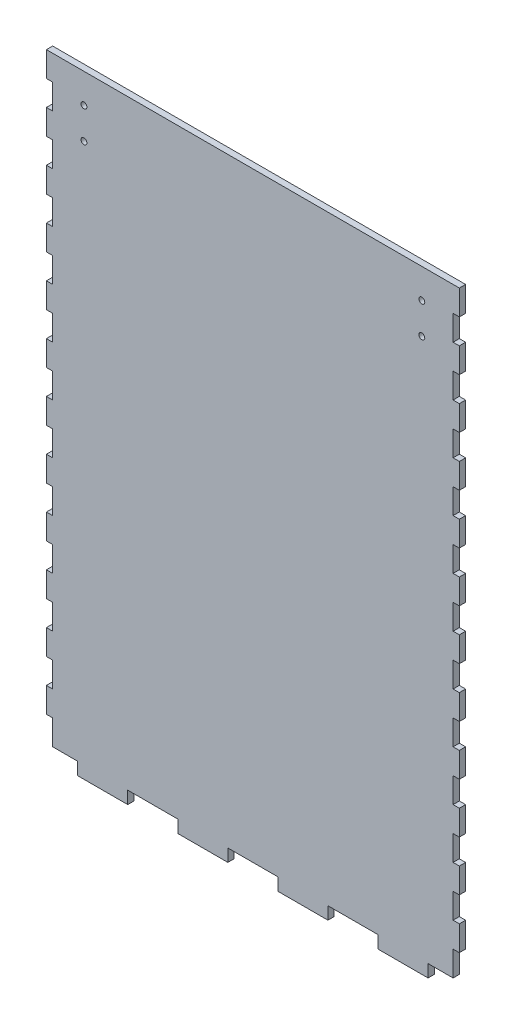
SolidWorks part; units mm, degrees
ref_plane "Front Plane" through (0, 0, 0) normal (0, 0, 1) x (1, 0, 0)
ref_plane "Top Plane" through (0, 0, 0) normal (0, 1, 0) x (1, 0, 0)
ref_plane "Right Plane" through (0, 0, 0) normal (1, 0, 0) x (0, 0, -1)
sketch "Sketch1" plane through (0, 0, 0) normal (0, 0, 1) x (1, 0, 0)
  line L0 (0, 0) -> (203.2, 0)
  line L1 (203.2, 0) -> (203.2, 304.8)
  line L2 (203.2, 304.8) -> (0, 304.8)
  line L3 (0, 304.8) -> (0, 0)
  dimension "D1" = 203.2
  dimension "D2" = 304.8
extrude "Boss-Extrude1" add sketch "Sketch1" along normal blind 3.175
sketch "Sketch2" plane through (0, 0, 3.175) normal (0, 0, 1) x (1, 0, 0)
  line L0 (0, 304.8) -> (-3.175, 304.8)
  line L1 (-3.175, 304.8) -> (-3.175, 292.1)
  line L2 (-3.175, 292.1) -> (0, 292.1)
  line L3 (0, 304.8) -> (0, 0) construction
  line L4 (0, 292.1) -> (0, 304.8)
  line L5 (101.6, 304.8) -> (101.6, 0) construction
  line L6 (203.2, 304.8) -> (0, 304.8) construction
  line L7 (0, 0) -> (203.2, 0) construction
  line L8 (206.375, 292.1) -> (203.2, 292.1)
  line L9 (206.375, 304.8) -> (206.375, 292.1)
  line L10 (203.2, 304.8) -> (206.375, 304.8)
  line L11 (203.2, 292.1) -> (203.2, 304.8)
  line L12 (0, 266.7) -> (0, 279.4)
  line L13 (0, 279.4) -> (-3.175, 279.4)
  line L14 (-3.175, 279.4) -> (-3.175, 266.7)
  line L15 (-3.175, 266.7) -> (0, 266.7)
  line L16 (206.375, 266.7) -> (203.2, 266.7)
  line L17 (203.2, 266.7) -> (203.2, 279.4)
  line L18 (203.2, 279.4) -> (206.375, 279.4)
  line L19 (206.375, 279.4) -> (206.375, 266.7)
  line L20 (0, 241.3) -> (0, 254)
  line L21 (0, 254) -> (-3.175, 254)
  line L22 (-3.175, 254) -> (-3.175, 241.3)
  line L23 (-3.175, 241.3) -> (0, 241.3)
  line L24 (206.375, 241.3) -> (203.2, 241.3)
  line L25 (203.2, 241.3) -> (203.2, 254)
  line L26 (203.2, 254) -> (206.375, 254)
  line L27 (206.375, 254) -> (206.375, 241.3)
  line L28 (0, 215.9) -> (0, 228.6)
  line L29 (0, 228.6) -> (-3.175, 228.6)
  line L30 (-3.175, 228.6) -> (-3.175, 215.9)
  line L31 (-3.175, 215.9) -> (0, 215.9)
  line L32 (206.375, 215.9) -> (203.2, 215.9)
  line L33 (203.2, 215.9) -> (203.2, 228.6)
  line L34 (203.2, 228.6) -> (206.375, 228.6)
  line L35 (206.375, 228.6) -> (206.375, 215.9)
  line L36 (0, 190.5) -> (0, 203.2)
  line L37 (0, 203.2) -> (-3.175, 203.2)
  line L38 (-3.175, 203.2) -> (-3.175, 190.5)
  line L39 (-3.175, 190.5) -> (0, 190.5)
  line L40 (206.375, 190.5) -> (203.2, 190.5)
  line L41 (203.2, 190.5) -> (203.2, 203.2)
  line L42 (203.2, 203.2) -> (206.375, 203.2)
  line L43 (206.375, 203.2) -> (206.375, 190.5)
  line L44 (0, 165.1) -> (0, 177.8)
  line L45 (0, 177.8) -> (-3.175, 177.8)
  line L46 (-3.175, 177.8) -> (-3.175, 165.1)
  line L47 (-3.175, 165.1) -> (0, 165.1)
  line L48 (206.375, 165.1) -> (203.2, 165.1)
  line L49 (203.2, 165.1) -> (203.2, 177.8)
  line L50 (203.2, 177.8) -> (206.375, 177.8)
  line L51 (206.375, 177.8) -> (206.375, 165.1)
  line L52 (0, 139.7) -> (0, 152.4)
  line L53 (0, 152.4) -> (-3.175, 152.4)
  line L54 (-3.175, 152.4) -> (-3.175, 139.7)
  line L55 (-3.175, 139.7) -> (0, 139.7)
  line L56 (206.375, 139.7) -> (203.2, 139.7)
  line L57 (203.2, 139.7) -> (203.2, 152.4)
  line L58 (203.2, 152.4) -> (206.375, 152.4)
  line L59 (206.375, 152.4) -> (206.375, 139.7)
  line L60 (0, 114.3) -> (0, 127)
  line L61 (0, 127) -> (-3.175, 127)
  line L62 (-3.175, 127) -> (-3.175, 114.3)
  line L63 (-3.175, 114.3) -> (0, 114.3)
  line L64 (206.375, 114.3) -> (203.2, 114.3)
  line L65 (203.2, 114.3) -> (203.2, 127)
  line L66 (203.2, 127) -> (206.375, 127)
  line L67 (206.375, 127) -> (206.375, 114.3)
  line L68 (0, 88.9) -> (0, 101.6)
  line L69 (0, 101.6) -> (-3.175, 101.6)
  line L70 (-3.175, 101.6) -> (-3.175, 88.9)
  line L71 (-3.175, 88.9) -> (0, 88.9)
  line L72 (206.375, 88.9) -> (203.2, 88.9)
  line L73 (203.2, 88.9) -> (203.2, 101.6)
  line L74 (203.2, 101.6) -> (206.375, 101.6)
  line L75 (206.375, 101.6) -> (206.375, 88.9)
  line L76 (0, 63.5) -> (0, 76.2)
  line L77 (0, 76.2) -> (-3.175, 76.2)
  line L78 (-3.175, 76.2) -> (-3.175, 63.5)
  line L79 (-3.175, 63.5) -> (0, 63.5)
  line L80 (206.375, 63.5) -> (203.2, 63.5)
  line L81 (203.2, 63.5) -> (203.2, 76.2)
  line L82 (203.2, 76.2) -> (206.375, 76.2)
  line L83 (206.375, 76.2) -> (206.375, 63.5)
  line L84 (0, 38.1) -> (0, 50.8)
  line L85 (0, 50.8) -> (-3.175, 50.8)
  line L86 (-3.175, 50.8) -> (-3.175, 38.1)
  line L87 (-3.175, 38.1) -> (0, 38.1)
  line L88 (206.375, 38.1) -> (203.2, 38.1)
  line L89 (203.2, 38.1) -> (203.2, 50.8)
  line L90 (203.2, 50.8) -> (206.375, 50.8)
  line L91 (206.375, 50.8) -> (206.375, 38.1)
  line L92 (0, 12.7) -> (0, 25.4)
  line L93 (0, 25.4) -> (-3.175, 25.4)
  line L94 (-3.175, 25.4) -> (-3.175, 12.7)
  line L95 (-3.175, 12.7) -> (0, 12.7)
  line L96 (206.375, 12.7) -> (203.2, 12.7)
  line L97 (203.2, 12.7) -> (203.2, 25.4)
  line L98 (203.2, 25.4) -> (206.375, 25.4)
  line L99 (206.375, 25.4) -> (206.375, 12.7)
  line L100 (0, 292.1) -> (0, 266.7) construction
  line L101 (12.7, 0) -> (12.7, -6.35)
  line L102 (12.7, -6.35) -> (38.1, -6.35)
  line L103 (38.1, -6.35) -> (38.1, 0)
  line L104 (38.1, 0) -> (12.7, 0)
  line L105 (88.9, 0) -> (63.5, 0)
  line L106 (63.5, 0) -> (63.5, -6.35)
  line L107 (63.5, -6.35) -> (88.9, -6.35)
  line L108 (88.9, -6.35) -> (88.9, 0)
  line L109 (139.7, 0) -> (114.3, 0)
  line L110 (114.3, 0) -> (114.3, -6.35)
  line L111 (114.3, -6.35) -> (139.7, -6.35)
  line L112 (139.7, -6.35) -> (139.7, 0)
  line L113 (190.5, 0) -> (165.1, 0)
  line L114 (165.1, 0) -> (165.1, -6.35)
  line L115 (165.1, -6.35) -> (190.5, -6.35)
  line L116 (190.5, -6.35) -> (190.5, 0)
  line L117 (38.1, 0) -> (88.9, 0) construction
  dimension "D1" = 3.175
  dimension "D2" = 12.7
  dimension "D4" = 25.4
  dimension "D5" = 12.7
  dimension "D6" = 6.35
  dimension "D7" = 25.4
  dimension "D9" = 50.8
  dimension "D3" = 12
  dimension "D8" = 4
extrude "Boss-Extrude2" add sketch "Sketch2" against normal up to surface (3.175 mm away) up to face at (101.6, 152.4, 0)
sketch "Sketch3" [suppressed] plane through (0, 0, 3.175) normal (0, 0, 1) x (1, 0, 0)
  line L0 (0, 0) -> (-3.175, 0)
  line L1 (-3.175, 0) -> (-3.175, 12.7)
  line L2 (-3.175, 12.7) -> (0, 12.7)
  line L3 (0, 304.8) -> (0, 0) construction
  line L4 (0, 12.7) -> (0, 0)
  line L5 (101.6, 304.8) -> (101.6, 0) construction
  line L6 (203.2, 304.8) -> (0, 304.8) construction
  line L7 (0, 0) -> (203.2, 0) construction
  line L8 (206.375, 12.7) -> (203.2, 12.7)
  line L9 (206.375, 0) -> (206.375, 12.7)
  line L10 (203.2, 0) -> (206.375, 0)
  line L11 (203.2, 12.7) -> (203.2, 0)
  line L12 (0, 38.1) -> (0, 25.4)
  line L13 (0, 25.4) -> (-3.175, 25.4)
  line L14 (-3.175, 25.4) -> (-3.175, 38.1)
  line L15 (-3.175, 38.1) -> (0, 38.1)
  line L16 (206.375, 38.1) -> (203.2, 38.1)
  line L17 (203.2, 38.1) -> (203.2, 25.4)
  line L18 (203.2, 25.4) -> (206.375, 25.4)
  line L19 (206.375, 25.4) -> (206.375, 38.1)
  line L20 (0, 63.5) -> (0, 50.8)
  line L21 (0, 50.8) -> (-3.175, 50.8)
  line L22 (-3.175, 50.8) -> (-3.175, 63.5)
  line L23 (-3.175, 63.5) -> (0, 63.5)
  line L24 (206.375, 63.5) -> (203.2, 63.5)
  line L25 (203.2, 63.5) -> (203.2, 50.8)
  line L26 (203.2, 50.8) -> (206.375, 50.8)
  line L27 (206.375, 50.8) -> (206.375, 63.5)
  line L28 (0, 88.9) -> (0, 76.2)
  line L29 (0, 76.2) -> (-3.175, 76.2)
  line L30 (-3.175, 76.2) -> (-3.175, 88.9)
  line L31 (-3.175, 88.9) -> (0, 88.9)
  line L32 (206.375, 88.9) -> (203.2, 88.9)
  line L33 (203.2, 88.9) -> (203.2, 76.2)
  line L34 (203.2, 76.2) -> (206.375, 76.2)
  line L35 (206.375, 76.2) -> (206.375, 88.9)
  line L36 (0, 114.3) -> (0, 101.6)
  line L37 (0, 101.6) -> (-3.175, 101.6)
  line L38 (-3.175, 101.6) -> (-3.175, 114.3)
  line L39 (-3.175, 114.3) -> (0, 114.3)
  line L40 (206.375, 114.3) -> (203.2, 114.3)
  line L41 (203.2, 114.3) -> (203.2, 101.6)
  line L42 (203.2, 101.6) -> (206.375, 101.6)
  line L43 (206.375, 101.6) -> (206.375, 114.3)
  line L44 (0, 139.7) -> (0, 127)
  line L45 (0, 127) -> (-3.175, 127)
  line L46 (-3.175, 127) -> (-3.175, 139.7)
  line L47 (-3.175, 139.7) -> (0, 139.7)
  line L48 (206.375, 139.7) -> (203.2, 139.7)
  line L49 (203.2, 139.7) -> (203.2, 127)
  line L50 (203.2, 127) -> (206.375, 127)
  line L51 (206.375, 127) -> (206.375, 139.7)
  line L52 (0, 165.1) -> (0, 152.4)
  line L53 (0, 152.4) -> (-3.175, 152.4)
  line L54 (-3.175, 152.4) -> (-3.175, 165.1)
  line L55 (-3.175, 165.1) -> (0, 165.1)
  line L56 (206.375, 165.1) -> (203.2, 165.1)
  line L57 (203.2, 165.1) -> (203.2, 152.4)
  line L58 (203.2, 152.4) -> (206.375, 152.4)
  line L59 (206.375, 152.4) -> (206.375, 165.1)
  line L60 (0, 190.5) -> (0, 177.8)
  line L61 (0, 177.8) -> (-3.175, 177.8)
  line L62 (-3.175, 177.8) -> (-3.175, 190.5)
  line L63 (-3.175, 190.5) -> (0, 190.5)
  line L64 (206.375, 190.5) -> (203.2, 190.5)
  line L65 (203.2, 190.5) -> (203.2, 177.8)
  line L66 (203.2, 177.8) -> (206.375, 177.8)
  line L67 (206.375, 177.8) -> (206.375, 190.5)
  line L68 (0, 215.9) -> (0, 203.2)
  line L69 (0, 203.2) -> (-3.175, 203.2)
  line L70 (-3.175, 203.2) -> (-3.175, 215.9)
  line L71 (-3.175, 215.9) -> (0, 215.9)
  line L72 (206.375, 215.9) -> (203.2, 215.9)
  line L73 (203.2, 215.9) -> (203.2, 203.2)
  line L74 (203.2, 203.2) -> (206.375, 203.2)
  line L75 (206.375, 203.2) -> (206.375, 215.9)
  line L76 (0, 241.3) -> (0, 228.6)
  line L77 (0, 228.6) -> (-3.175, 228.6)
  line L78 (-3.175, 228.6) -> (-3.175, 241.3)
  line L79 (-3.175, 241.3) -> (0, 241.3)
  line L80 (206.375, 241.3) -> (203.2, 241.3)
  line L81 (203.2, 241.3) -> (203.2, 228.6)
  line L82 (203.2, 228.6) -> (206.375, 228.6)
  line L83 (206.375, 228.6) -> (206.375, 241.3)
  line L84 (0, 266.7) -> (0, 254)
  line L85 (0, 254) -> (-3.175, 254)
  line L86 (-3.175, 254) -> (-3.175, 266.7)
  line L87 (-3.175, 266.7) -> (0, 266.7)
  line L88 (206.375, 266.7) -> (203.2, 266.7)
  line L89 (203.2, 266.7) -> (203.2, 254)
  line L90 (203.2, 254) -> (206.375, 254)
  line L91 (206.375, 254) -> (206.375, 266.7)
  line L92 (0, 292.1) -> (0, 279.4)
  line L93 (0, 279.4) -> (-3.175, 279.4)
  line L94 (-3.175, 279.4) -> (-3.175, 292.1)
  line L95 (-3.175, 292.1) -> (0, 292.1)
  line L96 (206.375, 292.1) -> (203.2, 292.1)
  line L97 (203.2, 292.1) -> (203.2, 279.4)
  line L98 (203.2, 279.4) -> (206.375, 279.4)
  line L99 (206.375, 279.4) -> (206.375, 292.1)
  line L100 (0, 12.7) -> (0, 38.1) construction
  line L101 (12.7, 0) -> (12.7, -6.35)
  line L102 (12.7, -6.35) -> (38.1, -6.35)
  line L103 (38.1, -6.35) -> (38.1, 0)
  line L104 (38.1, 0) -> (12.7, 0)
  line L105 (88.9, 0) -> (63.5, 0)
  line L106 (63.5, 0) -> (63.5, -6.35)
  line L107 (63.5, -6.35) -> (88.9, -6.35)
  line L108 (88.9, -6.35) -> (88.9, 0)
  line L109 (139.7, 0) -> (114.3, 0)
  line L110 (114.3, 0) -> (114.3, -6.35)
  line L111 (114.3, -6.35) -> (139.7, -6.35)
  line L112 (139.7, -6.35) -> (139.7, 0)
  line L113 (190.5, 0) -> (165.1, 0)
  line L114 (165.1, 0) -> (165.1, -6.35)
  line L115 (165.1, -6.35) -> (190.5, -6.35)
  line L116 (190.5, -6.35) -> (190.5, 0)
  line L117 (38.1, 0) -> (88.9, 0) construction
  dimension "D1" = 3.175
  dimension "D2" = 12.7
  dimension "D9" = 50.8
  dimension "D3" = 12
  dimension "D8" = 4
  dimension "D4" = 25.4
  dimension "D5" = 6.35
  dimension "D6" = 25.4
  dimension "D7" = 12.7
sketch "Sketch4" plane through (0, 0, 3.175) normal (0, 0, 1) x (1, 0, 0)
  line L0 (60, 33.5) -> (60, 66.5) construction
  line L1 (43.5, 50) -> (76.5, 50) construction
  line L2 (0, 12.7) -> (0, 0) construction
  line L3 (88.9, 0) -> (114.3, 0) construction
  circle A0 centre (60, 50) radius 16.5
  circle A1 centre (35, 75) radius 1.5
  circle A5 centre (85, 75) radius 1.5
  circle A6 centre (85, 25) radius 1.5
  circle A7 centre (35, 25) radius 1.5
  dimension "D5" = 33
  dimension "D6" = 3
  dimension "D1" = 50
  dimension "D2" = 50
  dimension "D3" = 60
  dimension "D4" = 50
extrude "Cut-Extrude1" [suppressed] cut sketch "Sketch4" against normal up to surface (3.175 mm away)
sketch "Sketch5" plane through (0, 0, 0) normal (0, 0, -1) x (-1, 0, 0)
  line L1 (-206.375, 304.8) -> (-206.375, 292.1) construction
  line L2 (-206.375, 304.8) -> (3.175, 304.8) construction
  line L3 (-101.6, 304.8) -> (-101.6, 0) construction
  line L4 (-88.9, 0) -> (-114.3, 0) construction
  circle A1 centre (-187.325, 289.8) radius 1.5
  circle A2 centre (-187.325, 274.05) radius 1.5
  circle A3 centre (-15.875, 274.05) radius 1.5
  circle A4 centre (-15.875, 289.8) radius 1.5
  dimension "D1" = 3
  dimension "D2" = 3
  dimension "D3" = 15.75
  dimension "D4" = 19.05
  dimension "D5" = 15
extrude "Cut-Extrude2" cut sketch "Sketch5" against normal up to surface (3.175 mm away) up to face at (101.6, 130.175, 3.175)
extrude "Boss-Extrude4" [suppressed] add sketch "Sketch3" against normal up to surface (3.175 mm away)
sketch "Sketch6" [suppressed] plane through (0, 0, 0) normal (0, 0, -1) x (-1, 0, 0)
  line L1 (-203.2, 304.8) -> (0, 304.8) construction
  line L2 (-101.6, 304.8) -> (-101.6, 0) construction
  line L3 (-88.9, 0) -> (-114.3, 0) construction
  line L4 (-206.375, 292.1) -> (-206.375, 279.4) construction
  circle A0 centre (-187.325, 289.8) radius 1.5
  circle A1 centre (-187.325, 274.05) radius 1.5
  circle A2 centre (-15.875, 274.05) radius 1.5
  circle A3 centre (-15.875, 289.8) radius 1.5
  dimension "D1" = 3
  dimension "D2" = 3
  dimension "D3" = 19.05
  dimension "D4" = 15
  dimension "D5" = 15.75
extrude "Cut-Extrude3" [suppressed] cut sketch "Sketch6" against normal up to surface (3.175 mm away)
equation "\"wall_thickness\"= 0.125in"
equation "\"base_thickness\"= 0.25in"
equation "\"D1@Boss-Extrude1\"=\"wall_thickness\""
equation "\"D1@Sketch2\"=\"wall_thickness\""
equation "\"D6@Sketch2\"=\"base_thickness\""
equation "\"D1@Sketch3\"=\"wall_thickness\""
equation "\"D5@Sketch3\"=\"base_thickness\""
